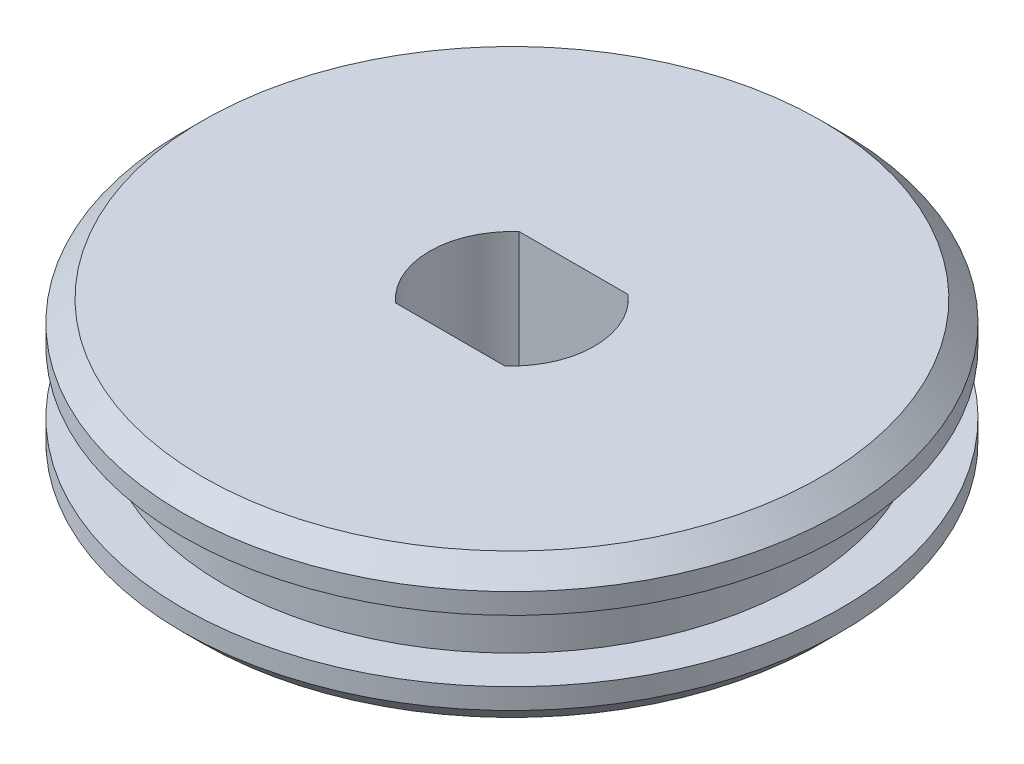
SolidWorks part; units mm, degrees
ref_plane "Alzado" through (0, 0, 0) normal (0, 0, 1) x (1, 0, 0)
ref_plane "Planta" through (0, 0, 0) normal (0, 1, 0) x (1, 0, 0)
ref_plane "Vista lateral" through (0, 0, 0) normal (1, 0, 0) x (0, 0, -1)
sketch "Croquis1" plane through (0, 0, 0) normal (0, 1, 0) x (1, 0, 0)
  circle A3 centre (0, 0) radius 16
  dimension "D1" = 32
extrude "Saliente-Extruir1" add sketch "Croquis1" along normal blind 2
sketch "Croquis4" plane through (0, 2, 0) normal (0, 1, 0) x (1, 0, 0)
  circle A0 centre (0, 0) radius 14
  dimension "D1" = 28
extrude "Saliente-Extruir2" add sketch "Croquis4" along normal blind 3
sketch "Croquis5" plane through (0, 5, 0) normal (0, 1, 0) x (1, 0, 0)
  circle A0 centre (0, 0) radius 16
  circle A1 centre (0, 0) radius 16 construction
extrude "Saliente-Extruir3" add sketch "Croquis5" along normal blind 2
sketch "Croquis6" plane through (0, 7, 0) normal (0, 1, 0) x (1, 0, 0)
  line L1 (-2.6458, -3) -> (2.6458, -3)
  line L3 (-2.6458, 3) -> (2.6458, 3)
  line L5 (-3.6754, -1.5783) -> (3.6754, 1.5783) construction
  line L6 (-3.6754, 1.5783) -> (3.6754, -1.5783) construction
  arc A0 (-2.6458, 3) -> (-2.6458, -3) centre (0, 0) ccw
  arc A1 (2.6458, -3) -> (2.6458, 3) centre (0, 0) ccw
  dimension "D1" = 8
extrude "Cortar-Extruir1" cut sketch "Croquis6" against normal through all
chamfer "Chaflán1" distance 1 angle 45 1 edges at (0, 7, 16)
chamfer "Chaflán2" distance 1 angle 45 1 edges at (0, 0, 16)
